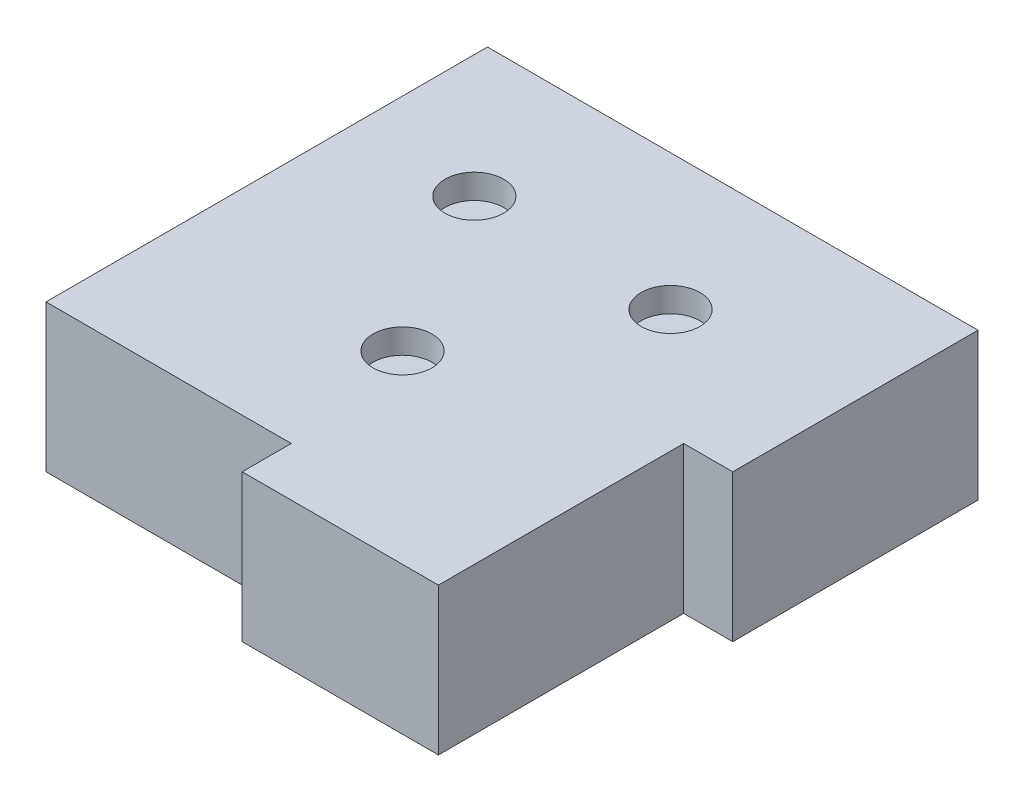
SolidWorks part; units mm, degrees
ref_plane "Front Plane" through (0, 0, 0) normal (0, 0, 1) x (1, 0, 0)
ref_plane "Top Plane" through (0, 0, 0) normal (0, 1, 0) x (1, 0, 0)
ref_plane "Right Plane" through (0, 0, 0) normal (1, 0, 0) x (0, 0, -1)
sketch "Sketch1" plane through (0, 0, 0) normal (0, 1, 0) x (1, 0, 0)
  line L0 (0, 10) -> (50, 10)
  line L1 (50, 0) -> (90, 0)
  line L2 (0, 10) -> (0, 100)
  line L3 (0, 100) -> (100, 100)
  line L4 (100, 50) -> (100, 100)
  line L5 (50, 10) -> (50, 0)
  line L8 (90, 0) -> (90, 50)
  line L9 (90, 50) -> (100, 50)
extrude "Boss-Extrude2" add sketch "Sketch1" along normal blind 30
sketch "Sketch3" plane through (0, 30, 0) normal (0, 1, 0) x (1, 0, 0)
  circle A0 centre (25, 72.32) radius 6
  circle A1 centre (65, 72.32) radius 6
  circle A2 centre (45, 37.68) radius 6
  point P6 (0, 0)
extrude "Cut-Extrude1" cut sketch "Sketch3" against normal blind 5
